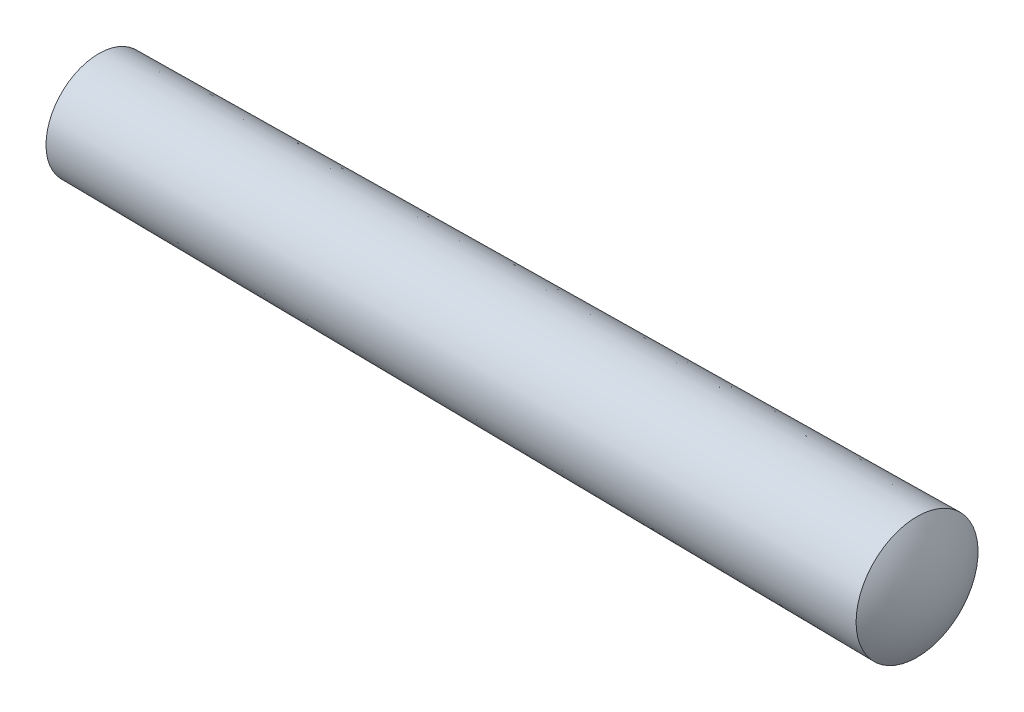
SolidWorks part; units mm, degrees
ref_plane "Plane1" through (0, 0, 0) normal (0, 0, 1) x (1, 0, 0)
ref_plane "Plane2" through (0, 0, 0) normal (0, 1, 0) x (1, 0, 0)
ref_plane "Plane3" through (0, 0, 0) normal (1, 0, 0) x (0, 0, -1)
sketch "BodySke" plane through (0, 0, 0) normal (0, 0, 1) x (1, 0, 0)
  line L0 (-0.6699, 0) -> (210, 0) construction
  line L1 (60, 0) -> (-0.6699, 0) construction
  line L2 (0, 2.5) -> (38.74, 2.8874)
  line L3 (0, 0) -> (0, 10) construction
  line L4 (-0.6699, 0) -> (39.658, 0)
  arc A0 (0, 2.5) -> (-0.6699, 0) centre (4.3301, 0) ccw
  arc A1 (38.74, 2.8874) -> (39.658, 0) centre (34.658, 0) cw
  dimension "D1" = 5
  dimension "D3" = 5
  dimension "D2" = 0.573
  dimension "Length" = 38.74
  dimension "Diameter" = 5
revolve "Body" add sketch "BodySke" angle 360 about L0
equation "\"D1@BodySke\" = \"Diameter@BodySke\""
equation "\"D3@BodySke\" = \"Diameter@BodySke\""
